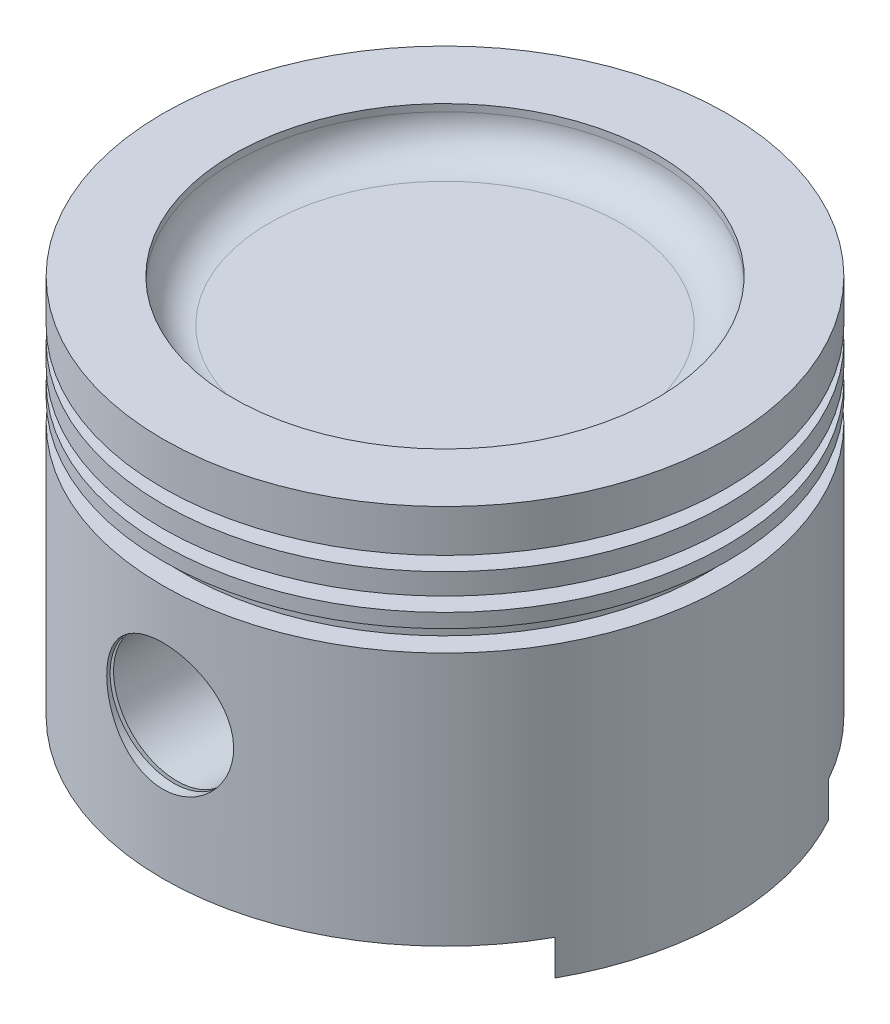
SolidWorks part; units mm, degrees
ref_plane "前视基准面" through (0, 0, 0) normal (0, 0, 1) x (1, 0, 0)
ref_plane "上视基准面" through (0, 0, 0) normal (0, 1, 0) x (1, 0, 0)
ref_plane "右视基准面" through (0, 0, 0) normal (1, 0, 0) x (0, 0, -1)
sketch "草图1" plane through (0, 0, 0) normal (0, 0, 1) x (1, 0, 0)
  line L0 (0, 53) -> (25, 53)
  line L1 (27, 0) -> (40, 0)
  line L2 (0, 46.5) -> (0, 53)
  line L3 (30, 59) -> (40, 59)
  line L4 (40, 0) -> (40, 41)
  line L5 (0, 46.5) -> (22, 46.5)
  line L6 (37, 53) -> (37, 51)
  line L7 (30, 59) -> (30, 58)
  line L8 (27, 41.5) -> (27, 0)
  line L9 (37, 53) -> (40, 53)
  line L10 (37, 51) -> (40, 51)
  line L11 (37, 48) -> (40, 48)
  line L12 (37, 46) -> (40, 46)
  line L13 (37, 44) -> (40, 44)
  line L14 (37, 41) -> (40, 41)
  line L15 (40, 53) -> (40, 59)
  line L16 (37, 48) -> (37, 46)
  line L17 (40, 48) -> (40, 51)
  line L18 (37, 44) -> (37, 41)
  line L19 (40, 44) -> (40, 46)
  line L20 (0, -5) -> (0, 65) construction
  arc A0 (30, 58) -> (25, 53) centre (25, 58) cw
  arc A1 (27, 41.5) -> (22, 46.5) centre (22, 41.5) ccw
  dimension "D16" = 5
  dimension "D1" = 59
  dimension "D2" = 40
  dimension "D3" = 6
  dimension "D4" = 6.5
  dimension "D5" = 3
  dimension "D6" = 10
  dimension "D7" = 6
  dimension "D13" = 70
  dimension "D14" = 5
  dimension "D15" = 13
  dimension "D8" = 2
  dimension "D9" = 3
  dimension "D10" = 2
  dimension "D11" = 2
  dimension "D12" = 3
revolve "旋转1" add sketch "草图1" angle 360 about L20
ref_plane "基准面1" through (0, 0, 13) normal (0, 0, 1) x (1, 0, 0)
sketch "草图2" plane through (0, 0, 13) normal (0, 0, 1) x (1, 0, 0)
  circle A1 centre (0, 25) radius 13
  dimension "D1" = 26
extrude "拉伸1" add sketch "草图2" along normal up to next
sketch "草图4" plane through (0, 0, 13) normal (0, 0, 1) x (1, 0, 0)
  circle A2 centre (0, 25) radius 9
  circle A3 centre (0, 25) radius 9
  dimension "D1" = 4
extrude "切除-拉伸2" cut sketch "草图4" along normal through all
ref_plane "基准面2" through (0, 0, 38) normal (0, 0, 1) x (1, 0, 0)
sketch "草图5" plane through (0, 0, 38) normal (0, 0, 1) x (1, 0, 0)
  circle A2 centre (0, 25) radius 10
  circle A3 centre (0, 25) radius 10
  dimension "D1" = 1
extrude "切除-拉伸3" cut sketch "草图5" along normal blind 0.5
sketch "草图7" plane through (0, 0, 13) normal (0, 0, -1) x (-1, 0, 0)
  line L0 (-13, 25) -> (-13, 46.5)
  line L1 (-13, 46.5) -> (13, 46.5)
  line L2 (13, 25) -> (13, 46.5)
  line L3 (-22, 46.5) -> (22, 46.5) construction
  circle A0 centre (0, 25) radius 13 construction
  arc A1 (13, 25) -> (-13, 25) centre (0, 25) ccw
extrude "凸台-拉伸1" add sketch "草图7" against normal up to next
mirror "镜向1" about plane through (0, 0, 0) normal (0, 0, 1) of "凸台-拉伸1", "切除-拉伸3", "拉伸1", "切除-拉伸2"
sketch "草图6" plane through (0, 0, 0) normal (0, 0, 1) x (1, 0, 0)
  line L1 (-35, 0) -> (35, 0)
  line L2 (-35, 0) -> (-35, 5)
  line L3 (-35, 5) -> (35, 5)
  line L4 (35, 0) -> (35, 5)
  dimension "D1" = 35
  dimension "D2" = 70
  dimension "D3" = 5
extrude "切除-拉伸4" cut sketch "草图6" against normal through all and the other way through all
